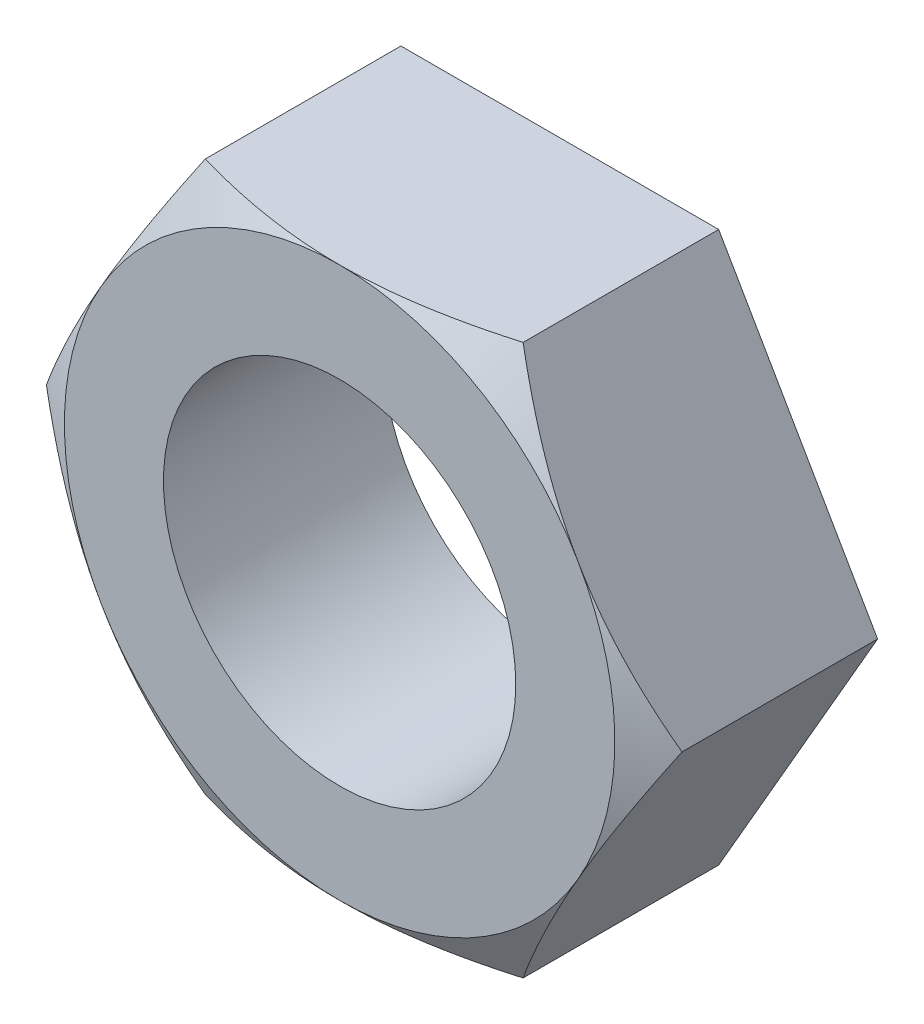
SolidWorks part; units mm, degrees
ref_plane "Ön Düzlem" through (0, 0, 0) normal (0, 0, 1) x (1, 0, 0)
ref_plane "Üst Düzlem" through (0, 0, 0) normal (0, 1, 0) x (1, 0, 0)
ref_plane "Sağ Düzlem" through (0, 0, 0) normal (1, 0, 0) x (0, 0, -1)
sketch "Çizim1" plane through (0, 0, 0) normal (0, 0, 1) x (1, 0, 0)
  line L1 (14.4338, 0) -> (7.2169, 12.5)
  line L2 (7.2169, 12.5) -> (-7.2169, 12.5)
  line L3 (-7.2169, 12.5) -> (-14.4338, 0)
  line L4 (-14.4338, 0) -> (-7.2169, -12.5)
  line L5 (-7.2169, -12.5) -> (7.2169, -12.5)
  line L6 (7.2169, -12.5) -> (14.4338, 0)
  circle A0 centre (0, 0) radius 12.5 construction
  dimension "D1" = 25
extrude "Yükseklik-Ekstrüzyon1" add sketch "Çizim1" along normal blind 10
sketch "Çizim2" plane through (0, 0, 10) normal (0, 0, 1) x (1, 0, 0)
  circle A0 centre (0, 0) radius 8
  dimension "D1" = 16
extrude "Kes-Ekstrüzyon1" cut sketch "Çizim2" against normal blind 10
sketch "Çizim3" plane through (0, 0, 10) normal (0, 0, 1) x (1, 0, 0)
  circle A0 centre (0, 0) radius 12.5
extrude "Kes-Ekstrüzyon2" cut sketch "Çizim3" against normal blind 10 draft 60 flip side to cut
